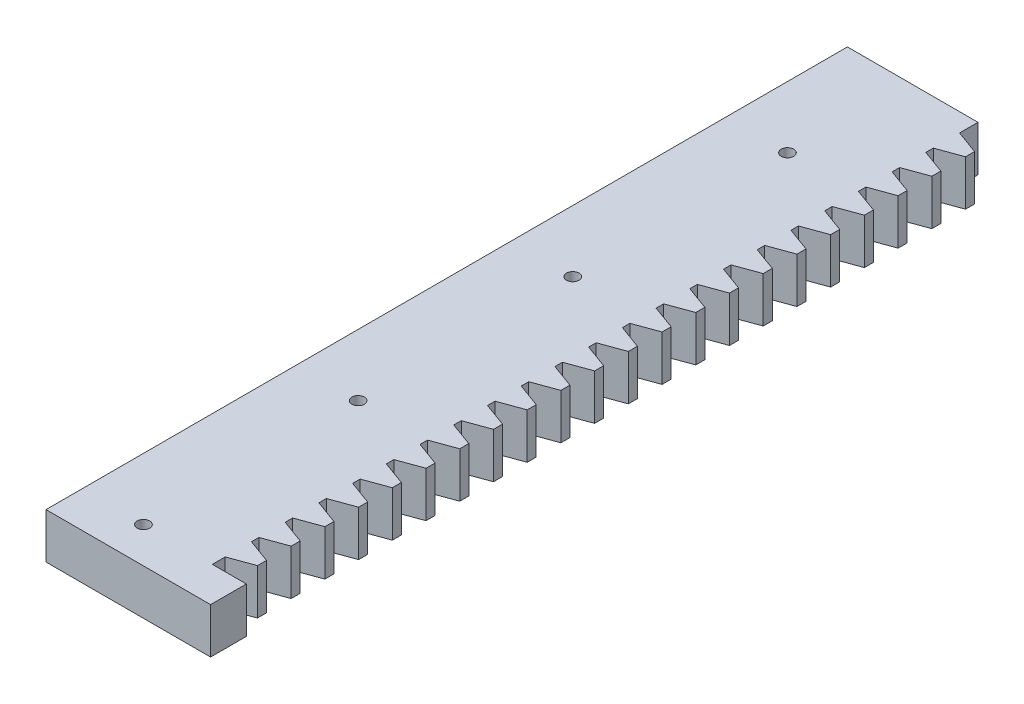
SolidWorks part; units mm, degrees
material "6061 Alloy"
ref_plane "Front Plane" through (0, 0, 0) normal (0, 0, 1) x (1, 0, 0)
ref_plane "Top Plane" through (0, 0, 0) normal (0, 1, 0) x (1, 0, 0)
ref_plane "Right Plane" through (0, 0, 0) normal (1, 0, 0) x (0, 0, -1)
sketch "Sketch1" plane through (0, 0, 0) normal (0, 1, 0) x (1, 0, 0)
  line L0 (0, 0) -> (0, 100)
  line L1 (0, 100) -> (18.25, 100) construction
  line L3 (18.25, 5) -> (23, 5)
  line L4 (23, 5) -> (23, 0)
  line L5 (23, 0) -> (0, 0)
  line L160 (18.25, 85.8629) -> (18.25, 86.9088)
  line L161 (18.25, 71.7257) -> (18.25, 72.7716)
  line L162 (18.25, 72.7716) -> (21.55, 73.9727)
  line L163 (21.55, 73.9727) -> (21.55, 75.237)
  line L164 (21.55, 75.237) -> (18.25, 76.4381)
  line L263 (18.25, 76.4381) -> (18.25, 77.484)
  line L265 (18.25, 77.484) -> (21.55, 78.6851)
  line L266 (21.55, 78.6851) -> (21.55, 79.9494)
  line L270 (21.55, 79.9494) -> (18.25, 81.1505)
  line L271 (18.25, 6.7983) -> (18.25, 5)
  line L272 (0, 100) -> (0, 112)
  line L273 (0, 112) -> (18.25, 112)
  line L275 (18.25, 100) -> (18.25, 101.0459)
  line L276 (18.25, 101.0459) -> (21.55, 102.247)
  line L277 (21.55, 102.247) -> (21.55, 103.5113)
  line L278 (21.55, 103.5113) -> (18.25, 104.7124)
  line L279 (18.25, 81.1505) -> (18.25, 82.1964)
  line L280 (18.25, 82.1964) -> (21.55, 83.3975)
  line L281 (21.55, 83.3975) -> (21.55, 84.6618)
  line L282 (21.55, 84.6618) -> (18.25, 85.8629)
  line L283 (18.25, 57.5886) -> (18.25, 58.6345)
  line L284 (18.25, 43.4514) -> (18.25, 44.4973)
  line L285 (18.25, 44.4973) -> (21.55, 45.6984)
  line L286 (21.55, 45.6984) -> (21.55, 46.9627)
  line L288 (21.55, 46.9627) -> (18.25, 48.1638)
  line L289 (18.25, 48.1638) -> (18.25, 49.2097)
  line L290 (18.25, 49.2097) -> (21.55, 50.4108)
  line L291 (21.55, 50.4108) -> (21.55, 51.6751)
  line L292 (21.55, 51.6751) -> (18.25, 52.8762)
  line L293 (18.25, 52.8762) -> (18.25, 53.9221)
  line L294 (18.25, 53.9221) -> (21.55, 55.1232)
  line L295 (21.55, 55.1232) -> (21.55, 56.3875)
  line L296 (21.55, 56.3875) -> (18.25, 57.5886)
  line L297 (18.25, 58.6345) -> (21.55, 59.8356)
  line L299 (21.55, 59.8356) -> (21.55, 61.0999)
  line L300 (21.55, 61.0999) -> (18.25, 62.301)
  line L301 (18.25, 62.301) -> (18.25, 63.3469)
  line L302 (18.25, 63.3469) -> (21.55, 64.548)
  line L303 (21.55, 64.548) -> (21.55, 65.8122)
  line L304 (21.55, 65.8122) -> (18.25, 67.0133)
  line L305 (18.25, 67.0133) -> (18.25, 68.0592)
  line L306 (18.25, 68.0592) -> (21.55, 69.2603)
  line L308 (21.55, 69.2603) -> (21.55, 70.5246)
  line L309 (21.55, 70.5246) -> (18.25, 71.7257)
  line L310 (18.25, 29.3143) -> (18.25, 30.3602)
  line L311 (18.25, 15.1772) -> (18.25, 16.2231)
  line L312 (18.25, 16.2231) -> (21.55, 17.4242)
  line L313 (21.55, 17.4242) -> (21.55, 18.6884)
  line L314 (21.55, 18.6884) -> (18.25, 19.8895)
  line L315 (18.25, 19.8895) -> (18.25, 20.9354)
  line L316 (18.25, 20.9354) -> (21.55, 22.1365)
  line L317 (21.55, 22.1365) -> (21.55, 23.4008)
  line L318 (21.55, 23.4008) -> (18.25, 24.6019)
  line L319 (18.25, 24.6019) -> (18.25, 25.6478)
  line L320 (18.25, 25.6478) -> (21.55, 26.8489)
  line L321 (21.55, 26.8489) -> (21.55, 28.1132)
  line L322 (21.55, 28.1132) -> (18.25, 29.3143)
  line L323 (18.25, 104.7124) -> (18.25, 105.7583)
  line L324 (18.25, 105.7583) -> (21.55, 106.9594)
  line L326 (21.55, 106.9594) -> (21.55, 108.2237)
  line L327 (21.55, 108.2237) -> (18.25, 109.4248)
  line L328 (18.25, 112) -> (18.25, 109.4248)
  line L343 (18.25, 6.7983) -> (21.55, 7.9994)
  line L344 (21.55, 7.9994) -> (21.55, 9.2637)
  line L345 (21.55, 9.2637) -> (18.25, 10.4648)
  line L346 (18.25, 10.4648) -> (18.25, 11.5107)
  line L347 (18.25, 11.5107) -> (21.55, 12.7118)
  line L348 (21.55, 12.7118) -> (21.55, 13.9761)
  line L349 (21.55, 13.9761) -> (18.25, 15.1772)
  line L350 (18.25, 30.3602) -> (21.55, 31.5613)
  line L352 (21.55, 31.5613) -> (21.55, 32.8256)
  line L353 (21.55, 32.8256) -> (18.25, 34.0267)
  line L354 (18.25, 34.0267) -> (18.25, 35.0726)
  line L356 (18.25, 35.0726) -> (21.55, 36.2737)
  line L357 (21.55, 36.2737) -> (21.55, 37.538)
  line L358 (21.55, 37.538) -> (18.25, 38.7391)
  line L359 (18.25, 38.7391) -> (18.25, 39.785)
  line L360 (18.25, 39.785) -> (21.55, 40.9861)
  line L361 (21.55, 40.9861) -> (21.55, 42.2503)
  line L363 (21.55, 42.2503) -> (18.25, 43.4514)
  line L428 (18.25, 86.9088) -> (21.55, 88.1099)
  line L429 (21.55, 88.1099) -> (21.55, 89.3741)
  line L430 (21.55, 89.3741) -> (18.25, 90.5752)
  line L431 (18.25, 90.5752) -> (18.25, 91.6211)
  line L432 (18.25, 91.6211) -> (21.55, 92.8222)
  line L433 (21.55, 92.8222) -> (21.55, 94.0865)
  line L434 (21.55, 94.0865) -> (18.25, 95.2876)
  line L435 (18.25, 95.2876) -> (18.25, 96.3335)
  line L436 (18.25, 96.3335) -> (21.55, 97.5346)
  line L437 (21.55, 97.5346) -> (21.55, 98.7989)
  line L438 (21.55, 98.7989) -> (18.25, 100)
  circle A56 centre (8.6192, 95) radius 0.875
  circle A59 centre (8.6192, 65) radius 0.875
  circle A62 centre (8.6192, 35) radius 0.875
  circle A65 centre (8.6192, 5) radius 0.875
  dimension "D1" = 1.75
  dimension "D4" = 1.75
  dimension "D6" = 1.75
  dimension "D7" = 1.75
  dimension "D2" = 100
  dimension "D5" = 4.75
  dimension "D20" = 5
  dimension "D3" = 12
extrude "Boss-Extrude1" add sketch "Sketch1" along normal blind 6.35
sketch "Sketch2" plane through (0, 0, -112) normal (0, 0, -1) x (-1, 0, 0)
  line L0 (-13.625, 3.175) -> (-4.625, 3.175) construction
  line L1 (-18.25, 6.35) -> (0, 6.35) construction
  line L2 (0, 6.35) -> (0, 0) construction
  circle A0 centre (-13.625, 3.175) radius 1.35
  circle A1 centre (-4.625, 3.175) radius 1.35
  point P4 (-9.125, 6.35)
  point P5 (-9.125, 3.175)
  point P8 (0, 3.175)
  dimension "D1" = 2.7
  dimension "D2" = 9
extrude "Cut-Extrude1" cut sketch "Sketch2" against normal blind 12
equation "\"D4@Sketch1\"=\"D1@Sketch1\""
equation "\"D6@Sketch1\"=\"D1@Sketch1\""
equation "\"D7@Sketch1\"=\"D1@Sketch1\""
